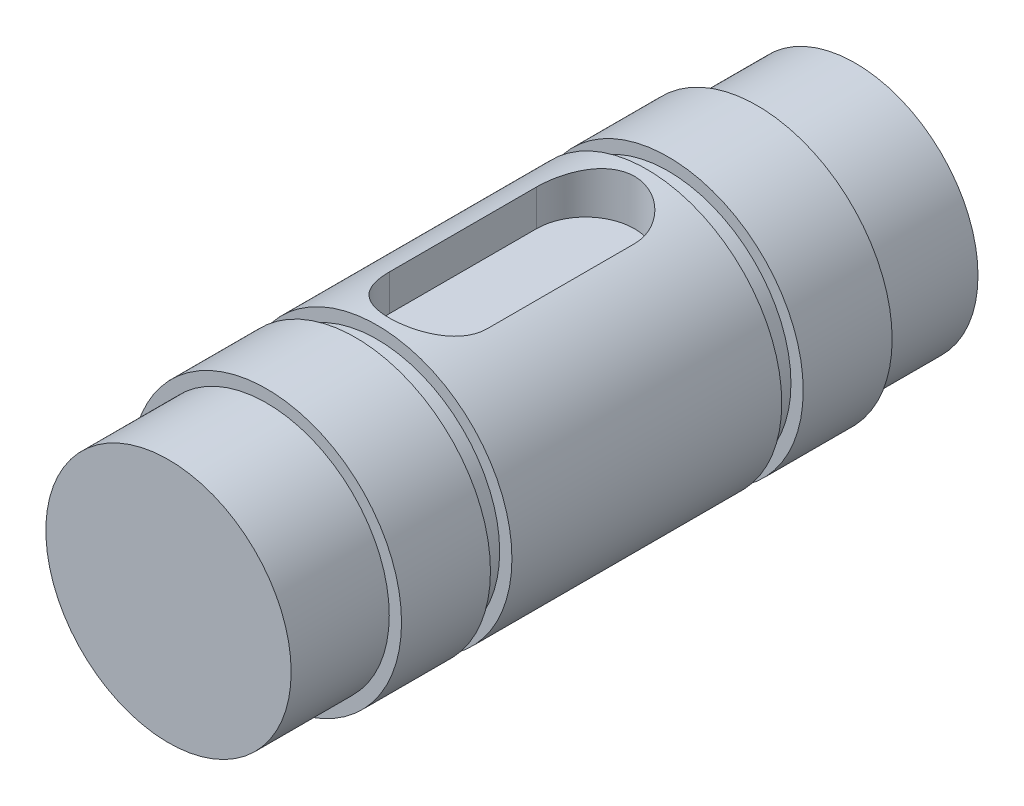
SolidWorks part; units mm, degrees
ref_plane "Front Plane" through (0, 0, 0) normal (0, 0, 1) x (1, 0, 0)
ref_plane "Top Plane" through (0, 0, 0) normal (0, 1, 0) x (1, 0, 0)
ref_plane "Right Plane" through (0, 0, 0) normal (1, 0, 0) x (0, 0, -1)
sketch "Sketch2" plane through (0, 0, 0) normal (0, 0, 1) x (1, 0, 0)
  circle A0 centre (0, 0) radius 11
extrude "Boss-Extrude1" add sketch "Sketch2" along normal blind 20
sketch "Sketch3" plane through (0, 0, 20) normal (0, 0, 1) x (1, 0, 0)
  circle A0 centre (0, 0) radius 10
extrude "Boss-Extrude2" add sketch "Sketch3" along normal blind 8
mirror "Mirror1" about plane through (0, 0, 0) normal (0, 0, 1) of bodies 102
ref_plane "Plane1" through (0, 11, 0) normal (0, 1, 0) x (1, 0, 0)
sketch "Sketch4" plane through (0, 11, 0) normal (0, 1, 0) x (1, 0, 0)
  line L0 (-4, -6) -> (4, -6)
  line L1 (-4, -6) -> (-4, 6)
  line L2 (4, -6) -> (4, 6)
  line L3 (-4, 6) -> (4, 6)
  line L4 (-4, -6) -> (4, 6) construction
  line L5 (4, -6) -> (-4, 6) construction
  arc A0 (-4, 6) -> (4, 6) centre (0, 6) cw
  arc A1 (-4, -6) -> (4, -6) centre (0, -6) ccw
  point P1 (0, 0)
  point P10 (0, 10)
  point P11 (0, -10)
  dimension "D1" = 8
  dimension "D2" = 20
extrude "Cut-Extrude1" cut sketch "Sketch4" against normal blind 3.7 contours L3 L1 L0 L2 | A0 L3 | L0 A1
ref_plane "Plane2" through (0, 0, 11) normal (0, 0, 1) x (1, 0, 0)
sketch "Sketch6" plane through (0, 0, 11) normal (0, 0, 1) x (1, 0, 0)
  circle A0 centre (0, 0) radius 10
extrude "Cut-Extrude4" cut sketch "Sketch6" along normal blind 1.75 flip side to cut
mirror "Mirror2" about plane through (0, 0, 0) normal (0, 0, 1) of "Cut-Extrude4"
